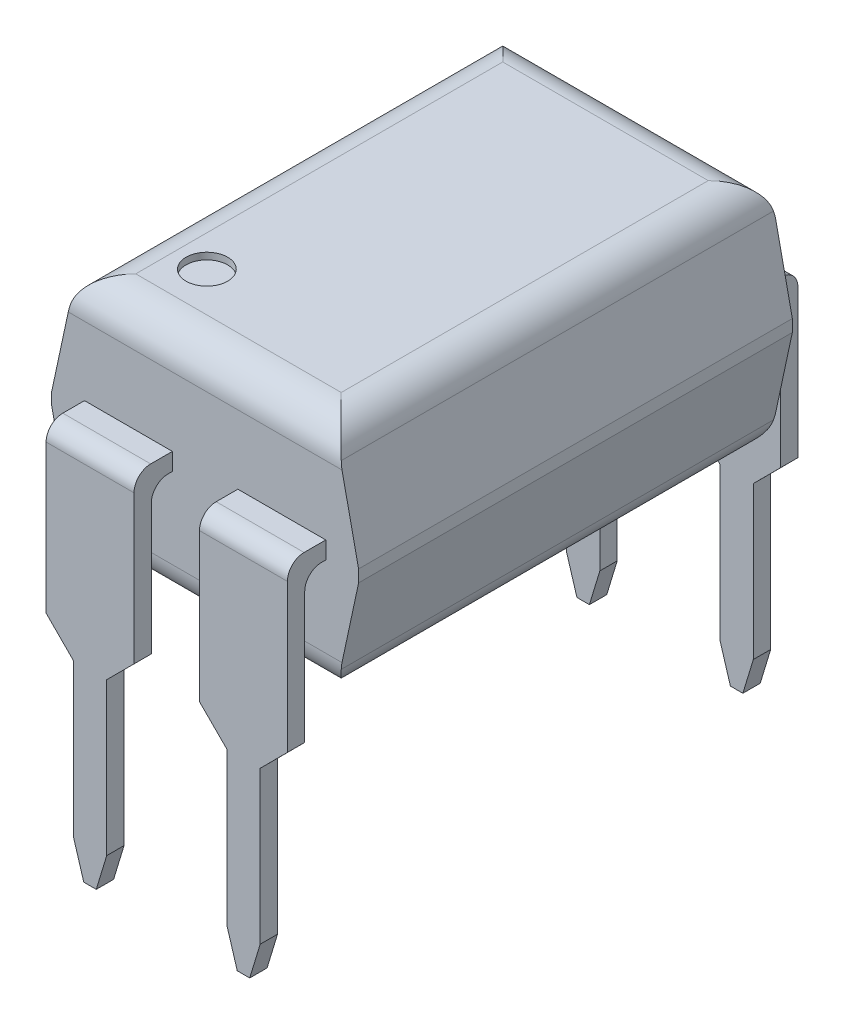
SolidWorks part; units mm, degrees
ref_plane "Front Plane" through (0, 0, 0) normal (0, 0, 1) x (1, 0, 0)
ref_plane "Top Plane" through (0, 0, 0) normal (0, 1, 0) x (1, 0, 0)
ref_plane "Right Plane" through (0, 0, 0) normal (1, 0, 0) x (0, 0, -1)
sketch "Sketch1" plane through (0, 0, 0) normal (0, 1, 0) x (1, 0, 0)
  line L1 (-2.3, -3.25) -> (2.3, -3.25)
  line L2 (-2.3, -3.25) -> (-2.3, 3.25)
  line L3 (-2.3, 3.25) -> (2.3, 3.25)
  line L4 (2.3, -3.25) -> (2.3, 3.25)
  line L5 (-2.3, -3.25) -> (2.3, 3.25) construction
  line L6 (-2.3, 3.25) -> (2.3, -3.25) construction
  point P0 (0, 0)
  dimension "D1" = 6.5
  dimension "D2" = 4.6
extrude "Boss-Extrude1" add sketch "Sketch1" along normal blind 3.5
sketch "Sketch2" plane through (0, 3.5, 0) normal (0, 1, 0) x (1, 0, 0)
  circle A0 centre (-1.0676, -2.1564) radius 0.3118
extrude "Cut-Extrude1" cut sketch "Sketch2" against normal blind 0.1
sketch "Sketch3" plane through (0, 0, 3.25) normal (0, 0, 1) x (1, 0, 0)
  line L0 (-2.3, 1.8406) -> (-1.9439, 3.5)
  line L1 (-2.3, 3.5) -> (-2.3, 0) construction
  line L2 (-2.3, 3.5) -> (2.3, 3.5) construction
  line L3 (0, 0) -> (0, 3.5) construction
  line L4 (-2.3, 1.75) -> (2.3, 1.75) construction
  line L5 (2.3, 3.5) -> (2.3, 0) construction
  line L6 (-2.3, 1.6594) -> (-1.9439, 0)
  line L7 (2.3, 1.6594) -> (1.9439, 0)
  line L8 (2.3, 1.8406) -> (1.9439, 3.5)
  line L9 (-1.9439, 3.5) -> (1.9439, 3.5)
  line L10 (1.9439, 0) -> (-1.9439, 0)
  line L11 (2.3, 1.6594) -> (2.3, 1.8406)
  line L12 (-2.3, 1.8406) -> (-2.3, 1.6594)
extrude "Cut-Extrude3" cut sketch "Sketch3" against normal through all flip side to cut
fillet "Fillet1" radius 0.5 8 edges at (1.9439, 0, 0) (-1.9439, 0, 0) (1.9439, 3.5, 0) (-1.9439, 3.5, 0) (0, 0, -3.25) (0, 3.5, -3.25) (0, 0, 3.25) (0, 3.5, 3.25)
sketch "Sketch4" plane through (-2.3, 0, 0) normal (-1, 0, 0) x (0, 0, 1)
  line L0 (-3.8251, -3.7094) -> (-3.5651, -3.7094)
  line L2 (-3.25, 1.8406) -> (3.25, 1.8406) construction
  line L3 (3.5651, -3.7094) -> (3.8251, -3.7094)
  line L4 (0, 3.5) -> (0, -1.2461) construction
  line L5 (-2.75, 3.5) -> (2.75, 3.5) construction
  line L7 (3.8251, 1.7206) -> (3.8251, -3.7094)
  line L8 (3.5751, 1.9706) -> (-3.5751, 1.9706)
  line L9 (-3.8251, 1.7206) -> (-3.8251, -3.7094)
  line L10 (3.5651, 1.4606) -> (3.5651, -3.7094)
  line L11 (3.3151, 1.7106) -> (-3.3151, 1.7106)
  line L12 (-3.5651, 1.4606) -> (-3.5651, -3.7094)
  arc A0 (3.5651, 1.4606) -> (3.3151, 1.7106) centre (3.3151, 1.4606) ccw
  arc A1 (3.8251, 1.7206) -> (3.5751, 1.9706) centre (3.5751, 1.7206) ccw
  arc A2 (-3.5751, 1.9706) -> (-3.8251, 1.7206) centre (-3.5751, 1.7206) ccw
  arc A3 (-3.3151, 1.7106) -> (-3.5651, 1.4606) centre (-3.3151, 1.4606) ccw
  point P5 (0, 1.8406)
  point P6 (0, 1.8406)
  dimension "D1" = 0.25
extrude "Boss-Extrude2" add sketch "Sketch4" against normal through all separate body
sketch "Sketch5" plane through (0, 0, -3.8251) normal (0, 0, -1) x (-1, 0, 0)
  line L0 (0, 1.7206) -> (0, -4.1057) construction
  line L1 (-2.3, 1.7206) -> (2.3, 1.7206) construction
  line L2 (-1.15, -3.7094) -> (-1.15, -0.9094) construction
  line L3 (-2.3, -3.7094) -> (2.3, -3.7094) construction
  line L4 (-0.9, -3.1928) -> (-0.9, -0.9094)
  line L5 (1.4, -0.9094) -> (1.8078, -0.5)
  line L7 (-0.9, -0.9094) -> (-0.4905, -0.5)
  line L8 (-1.4, -3.1928) -> (-1.4, -0.9094)
  line L9 (-1.4, -0.9094) -> (-1.8078, -0.5)
  line L10 (-1.8078, -0.5) -> (-1.8078, 1.7206)
  line L11 (-0.4905, -0.5) -> (-0.4905, 1.7206)
  line L12 (-1.8078, 1.9731) -> (-1.8078, 1.7206)
  line L13 (-0.4905, 1.7206) -> (-0.4905, 1.9731)
  line L14 (-0.4905, 1.9731) -> (-1.8078, 1.9731)
  line L15 (-1.0565, -3.7094) -> (-0.9, -3.1928)
  line L16 (-1.2435, -3.7094) -> (-1.4, -3.1928)
  line L17 (-1.2435, -3.7094) -> (-1.0565, -3.7094)
  line L18 (1.4, -3.1928) -> (1.4, -0.9094)
  line L19 (1.2435, -3.7094) -> (1.4, -3.1928)
  line L20 (1.2435, -3.7094) -> (1.0565, -3.7094)
  line L21 (1.0565, -3.7094) -> (0.9, -3.1928)
  line L22 (0.9, -0.9094) -> (0.4905, -0.5)
  line L23 (0.9, -3.1928) -> (0.9, -0.9094)
  line L24 (0.4905, 1.7206) -> (0.4905, 1.9731)
  line L25 (0.4905, -0.5) -> (0.4905, 1.7206)
  line L26 (0.4905, 1.9731) -> (1.8078, 1.9731)
  line L27 (1.8078, 1.9731) -> (1.8078, 1.7206)
  line L28 (1.8078, -0.5) -> (1.8078, 1.7206)
  point P16 (0, -0.5)
extrude "Cut-Extrude7" cut sketch "Sketch5" against normal through all both and the other way through all flip side to cut
